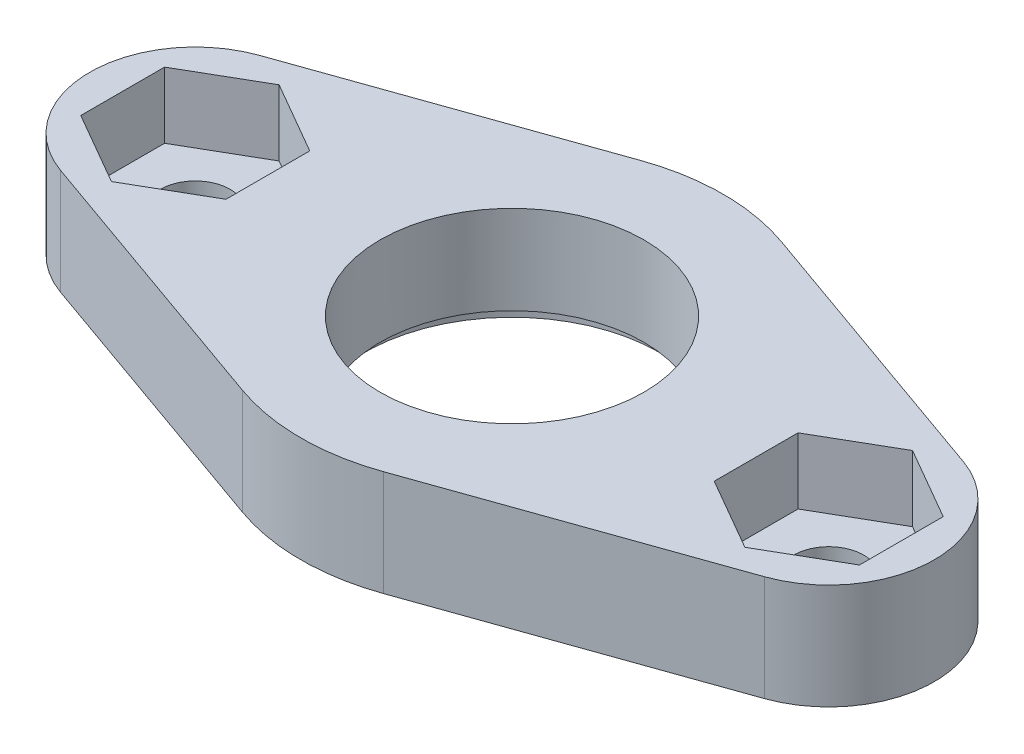
SolidWorks part; units mm, degrees
ref_plane "Front" through (0, 0, 0) normal (0, 0, 1) x (1, 0, 0)
ref_plane "Top" through (0, 0, 0) normal (0, 1, 0) x (1, 0, 0)
ref_plane "Right" through (0, 0, 0) normal (1, 0, 0) x (0, 0, -1)
sketch "Sketch1" plane through (0, 0, 0) normal (0, 1, 0) x (1, 0, 0)
  line L0 (19.05, 0) -> (-19.05, 0) construction
  line L9 (-21.1667, 5.9868) -> (-4.2333, 11.9737)
  line L10 (4.2333, 11.9737) -> (21.1667, 5.9868)
  line L11 (-21.1667, -5.9868) -> (-4.2333, -11.9737)
  line L12 (21.1667, -5.9868) -> (4.2333, -11.9737)
  circle A1 centre (0, 0) radius 7.9375
  circle A3 centre (-19.05, 0) radius 2.0955
  circle A4 centre (19.05, 0) radius 2.0955
  arc A5 (-21.1667, 5.9868) -> (-21.1667, -5.9868) centre (-19.05, 0) ccw
  arc A6 (21.1667, -5.9868) -> (21.1667, 5.9868) centre (19.05, 0) ccw
  arc A7 (4.2333, 11.9737) -> (-4.2333, 11.9737) centre (0, 0) ccw
  arc A9 (-4.2333, -11.9737) -> (4.2333, -11.9737) centre (0, 0) ccw
  point P6 (12.7, 0)
  point P12 (0, 0)
  dimension "D1" = 15.875
  dimension "D4" = 12.7
  dimension "D5" = 4.191
  dimension "D7" = 12.7
  dimension "D6" = 38.1
extrude "whole-part" add sketch "Sketch1" along normal blind 6.35
sketch "Sketch2" plane through (0, 0, 0) normal (0, -1, 0) x (-1, 0, 0)
  circle A0 centre (0, 0) radius 8.89
  dimension "D1" = 17.78
extrude "bearing-depth" cut sketch "Sketch2" against normal blind 1.016
sketch "Sketch3" plane through (0, 6.35, 0) normal (0, 1, 0) x (1, 0, 0)
  line L1 (-23.4156, 2.5205) -> (-23.4156, -2.5205)
  line L2 (-23.4156, -2.5205) -> (-19.05, -5.041)
  line L3 (-19.05, -5.041) -> (-14.6844, -2.5205)
  line L4 (-14.6844, -2.5205) -> (-14.6844, 2.5205)
  line L5 (-14.6844, 2.5205) -> (-19.05, 5.041)
  line L6 (-19.05, 5.041) -> (-23.4156, 2.5205)
  line L7 (19.05, 5.041) -> (14.6844, 2.5205)
  line L8 (14.6844, 2.5205) -> (14.6844, -2.5205)
  line L9 (14.6844, -2.5205) -> (19.05, -5.041)
  line L10 (19.05, -5.041) -> (23.4156, -2.5205)
  line L11 (23.4156, -2.5205) -> (23.4156, 2.5205)
  line L12 (23.4156, 2.5205) -> (19.05, 5.041)
  circle A0 centre (-19.05, 0) radius 4.3656 construction
  circle A1 centre (19.05, 0) radius 4.3656 construction
  dimension "D1" = 8.7312
extrude "nut-pocket" cut sketch "Sketch3" against normal blind 3.9688
